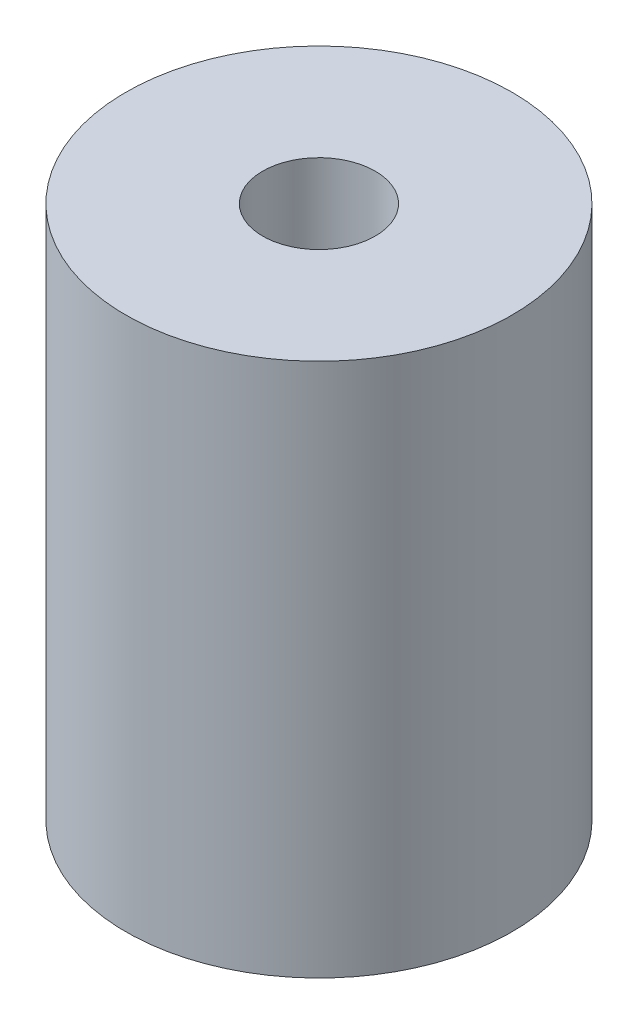
SolidWorks part; units mm, degrees
material "ABS PC"
ref_plane "Front Plane" through (0, 0, 0) normal (0, 0, 1) x (1, 0, 0)
ref_plane "Top Plane" through (0, 0, 0) normal (0, 1, 0) x (1, 0, 0)
ref_plane "Right Plane" through (0, 0, 0) normal (1, 0, 0) x (0, 0, -1)
sketch "Sketch1" plane through (0, 0, 0) normal (0, 1, 0) x (1, 0, 0)
  circle A0 centre (0, 0) radius 1.75
  circle A1 centre (0, 0) radius 6
  dimension "D1" = 3.5
  dimension "D2" = 12
extrude "Boss-Extrude1" add sketch "Sketch1" along normal mid plane 16.6
